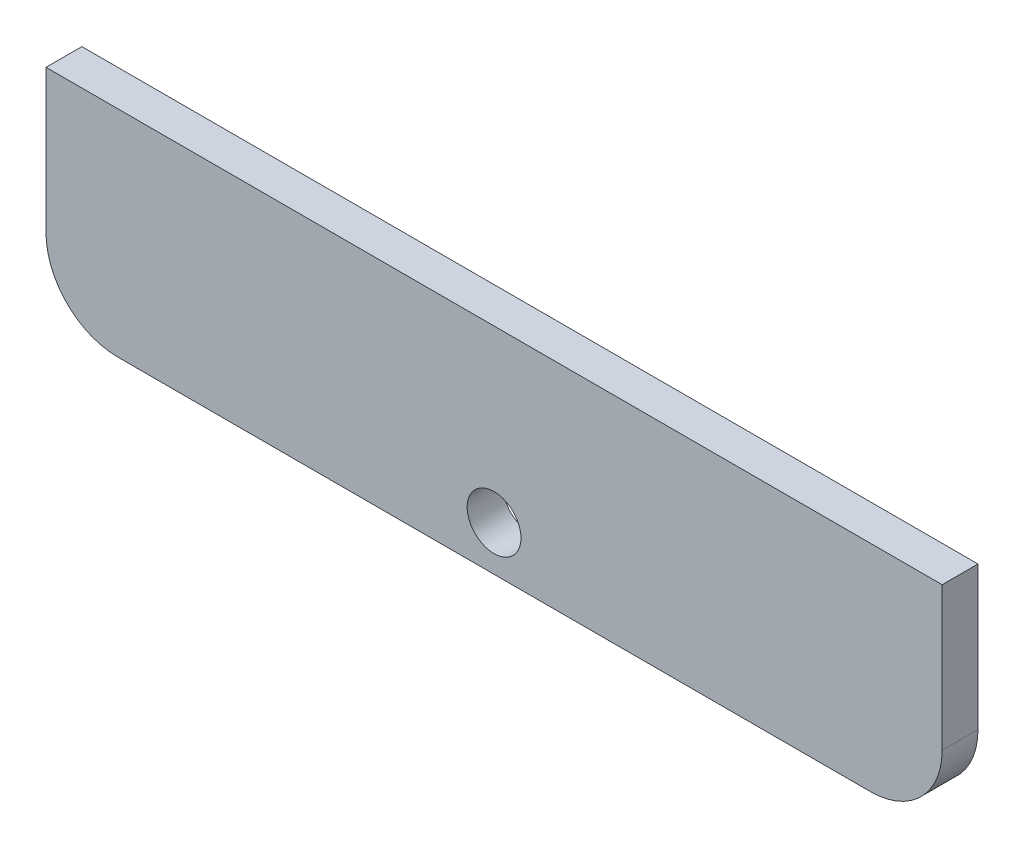
SolidWorks part; units mm, degrees
ref_plane "Front Plane" through (0, 0, 0) normal (0, 0, 1) x (1, 0, 0)
ref_plane "Top Plane" through (0, 0, 0) normal (0, 1, 0) x (1, 0, 0)
ref_plane "Right Plane" through (0, 0, 0) normal (1, 0, 0) x (0, 0, -1)
sketch "Sketch1" plane through (0, 0, 0) normal (0, 0, 1) x (1, 0, 0)
  line L1 (-21, -2.5) -> (21, -2.5)
  line L10 (-25, 1.5) -> (-25, 9.5)
  line L11 (-25, 9.5) -> (25, 9.5)
  line L12 (25, 1.5) -> (25, 9.5)
  circle A0 centre (0, 0) radius 1.5
  arc A1 (25, 1.5) -> (21, -2.5) centre (21, 1.5) cw
  arc A2 (-21, -2.5) -> (-25, 1.5) centre (-21, 1.5) cw
  point P0 (0, 0)
  dimension "D1" = 3
  dimension "D4" = 4
  dimension "D2" = 2.5
  dimension "D3" = 12
  dimension "D5" = 50
  dimension "D6" = 25
extrude "Boss-Extrude1" add sketch "Sketch1" along normal mid plane 2
